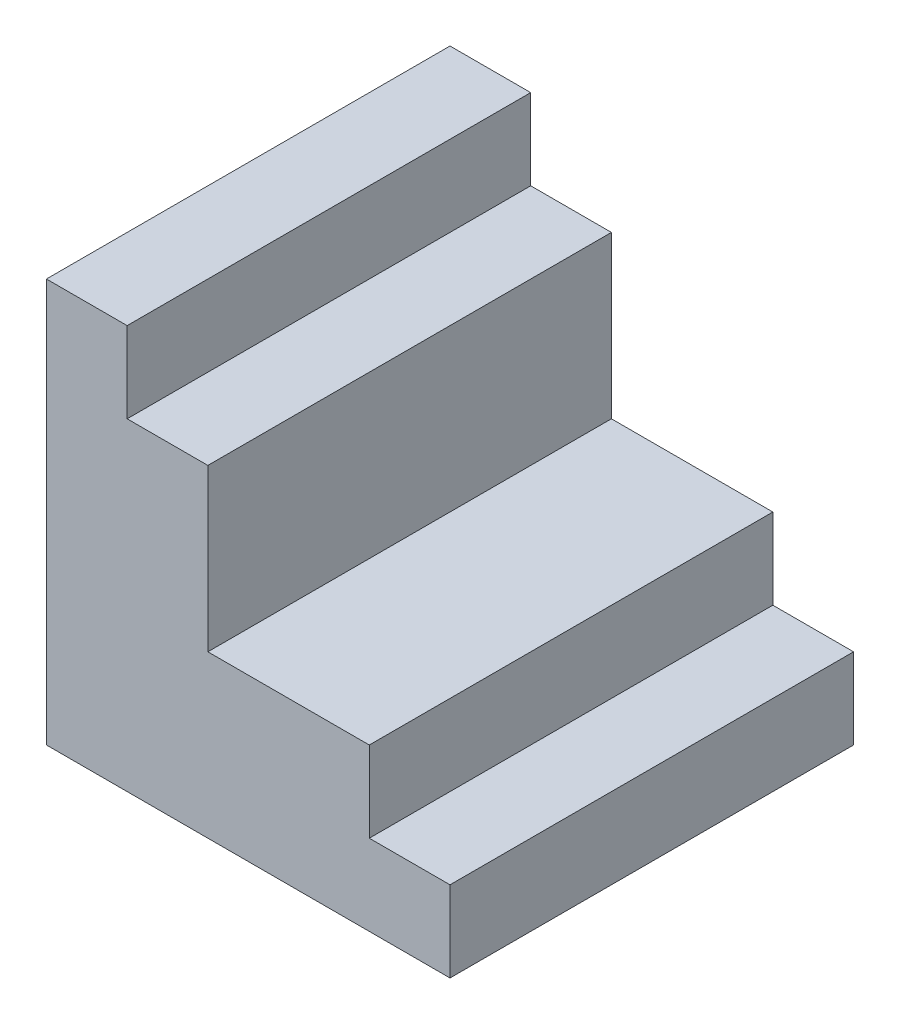
SolidWorks part; units mm, degrees
ref_plane "Front Plane" through (0, 0, 0) normal (0, 0, 1) x (1, 0, 0)
ref_plane "Top Plane" through (0, 0, 0) normal (0, 1, 0) x (1, 0, 0)
ref_plane "Right Plane" through (0, 0, 0) normal (1, 0, 0) x (0, 0, -1)
sketch "Sketch1" plane through (0, 0, 0) normal (0, 0, 1) x (1, 0, 0)
  line L0 (-5, 10) -> (-5, 0)
  line L1 (-5, 0) -> (5, 0)
  line L2 (-5, 10) -> (-3, 10)
  line L3 (-3, 10) -> (-3, 8)
  line L4 (-3, 8) -> (-1, 8)
  line L5 (-1, 8) -> (-1, 4)
  line L6 (-1, 4) -> (3, 4)
  line L7 (3, 4) -> (3, 2)
  line L8 (3, 2) -> (5, 2)
  line L9 (5, 2) -> (5, 0)
  point P2 (0, 0)
  dimension "D1" = 10
  dimension "D2" = 10
  dimension "D3" = 2
  dimension "D4" = 2
  dimension "D5" = 2
  dimension "D6" = 4
  dimension "D7" = 4
  dimension "D8" = 2
extrude "Boss-Extrude1" add sketch "Sketch1" along normal mid plane 10
